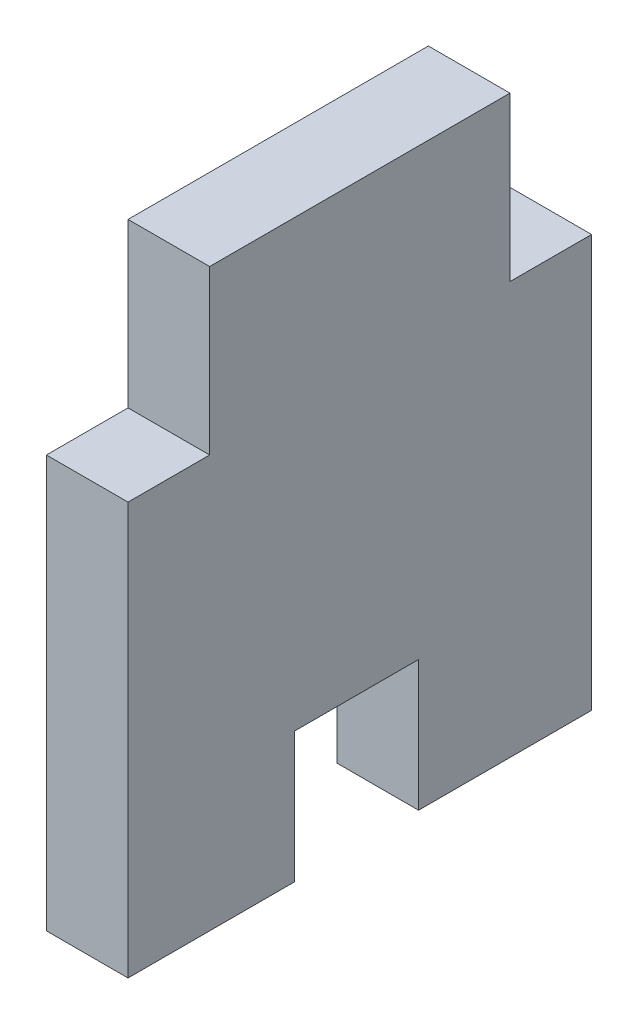
SolidWorks part; units mm, degrees
material "Balsa"
ref_plane "Front Plane" through (0, 0, 0) normal (0, 0, 1) x (1, 0, 0)
ref_plane "Top Plane" through (0, 0, 0) normal (0, 1, 0) x (1, 0, 0)
ref_plane "Right Plane" through (0, 0, 0) normal (1, 0, 0) x (0, 0, -1)
sketch "Sketch1" plane through (0, 0, 0) normal (1, 0, 0) x (0, 0, -1)
  line L0 (0, 0) -> (0, 12.7) construction
  line L1 (11.684, 12.7) -> (-11.684, 12.7)
  line L2 (-11.684, 12.7) -> (-11.684, 0)
  line L3 (-11.684, 0) -> (-18.034, 0)
  line L4 (-18.034, 0) -> (-18.034, -32.0675)
  line L7 (11.684, 12.7) -> (11.684, 0)
  line L8 (11.684, 0) -> (18.034, 0)
  line L9 (18.034, 0) -> (18.034, -32.0675)
  line L13 (-18.034, -32.0675) -> (-5.08, -32.0675)
  line L14 (-5.08, -32.0675) -> (-5.08, -21.9075)
  line L15 (-5.08, -21.9075) -> (4.572, -21.9075)
  line L16 (4.572, -21.9075) -> (4.572, -32.0675)
  line L17 (4.572, -32.0675) -> (18.034, -32.0675)
  point P5 (0, 12.7)
  dimension "D1" = 12.7
  dimension "D2" = 6.35
  dimension "D3" = 6.35
  dimension "D4" = 12.954
  dimension "D5" = 9.652
  dimension "D7" = 10.16
extrude "Boss-Extrude1" add sketch "Sketch1" along normal blind 6.35
